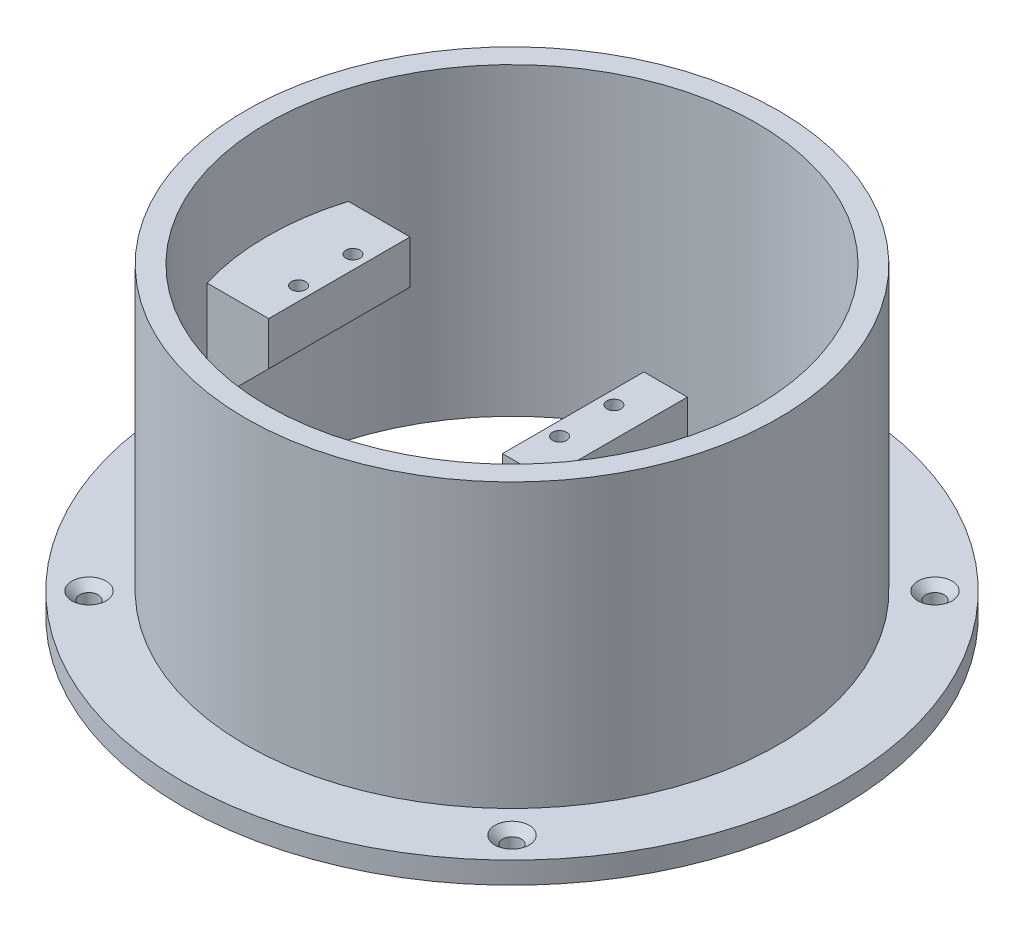
SolidWorks part; units mm, degrees
material "ABS"
ref_plane "Front Plane" through (0, 0, 0) normal (0, 0, 1) x (1, 0, 0)
ref_plane "Top Plane" through (0, 0, 0) normal (0, 1, 0) x (1, 0, 0)
ref_plane "Right Plane" through (0, 0, 0) normal (1, 0, 0) x (0, 0, -1)
sketch "Sketch1" plane through (0, 0, 0) normal (0, 1, 0) x (1, 0, 0)
  circle A0 centre (0, 0) radius 60.625
  circle A1 centre (0, 0) radius 45
  dimension "D1" = 121.25
  dimension "D2" = 90
extrude "Boss-Extrude1" add sketch "Sketch1" along normal blind 4 contours A0
sketch "Sketch2" plane through (0, 4, 0) normal (0, 1, 0) x (1, 0, 0)
  circle A0 centre (0, 0) radius 45 construction
  circle A1 centre (0, 0) radius 45
  circle A2 centre (0, 0) radius 49
  dimension "D1" = 4
extrude "Boss-Extrude2" add sketch "Sketch2" along normal blind 52
ref_plane "Plane1" through (0, 36, 0) normal (0, 1, 0) x (1, 0, 0)
sketch "Sketch4" plane through (0, 0, 0) normal (0, 0, 1) x (1, 0, 0)
  line L0 (-60.625, 0) -> (60.625, 0) construction
  line L1 (11.25, 38) -> (19.25, 38)
  line L2 (11.25, 38) -> (11.25, 0)
  line L3 (11.25, 0) -> (19.25, 0)
  line L4 (19.25, 38) -> (19.25, 0)
  line L5 (49, 56) -> (-49, 56) construction
  line L6 (-45, 56) -> (-45, 4)
  line L7 (-31.75, 38) -> (-46.75, 38)
  line L8 (-31.75, 38) -> (-31.75, 30)
  line L9 (-31.75, 30) -> (-46.75, 30)
  line L10 (-46.75, 38) -> (-46.75, 30)
  line L11 (60.625, 4) -> (-60.625, 4) construction
  line L12 (-31.75, 30) -> (-45, 16.75)
  dimension "D1" = 11.25
  dimension "D2" = 8
  dimension "D3" = 18
  dimension "D4" = 43
  dimension "D5" = 15
  dimension "D6" = 8
  dimension "D7" = 45
  dimension "D8" = 18
extrude "Boss-Extrude4" add sketch "Sketch4" along normal mid plane 26 contours L9 L8 L7 L6 | L12 L9 L6 | L1 L4 L3 L2
sketch "Sketch5" plane through (0, 0, 0) normal (0, -1, 0) x (1, 0, 0)
  line L0 (11.25, 13) -> (29.0674, 34.3524)
  line L1 (11.25, -13) -> (29.0674, -34.3524)
  line L2 (11.25, 13) -> (11.25, -13)
  circle A0 centre (0, 0) radius 45 construction
  arc A1 (29.0674, -34.3524) -> (29.0674, 34.3524) centre (0, 0) ccw
extrude "Boss-Extrude5" add sketch "Sketch5" against normal up to surface (4 mm away) contours L0 A1 L1 L2 up to face at (0, 4, 60.625)
sketch "Sketch7" plane through (0, 38, 0) normal (0, 1, 0) x (1, 0, 0)
  line L0 (-31.75, -13) -> (-31.75, 13) construction
  circle A0 centre (-34.25, 5) radius 1.3
  circle A1 centre (-34.25, -5) radius 1.3
  circle A2 centre (13.75, 5) radius 1.3
  circle A3 centre (13.75, -5) radius 1.3
  dimension "D1" = 2.6
  dimension "D2" = 2.6
  dimension "D3" = 10
  dimension "D4" = 5
  dimension "D5" = 2.5
  dimension "D7" = 48
  dimension "D6" = 2
extrude "Cut-Extrude4" cut sketch "Sketch7" against normal blind 7.2
sketch "Sketch9" plane through (11.25, 0, 0) normal (-1, 0, 0) x (0, 0, 1)
  line L0 (13, 0) -> (-13, 0) construction
  line L1 (-5, 29) -> (5, 29)
  line L2 (-5, 29) -> (-5, 0)
  line L3 (-5, 0) -> (5, 0)
  line L4 (5, 29) -> (5, 0)
  line L5 (-5, 29) -> (5, 0) construction
  line L6 (-5, 0) -> (5, 29) construction
  line L7 (0, 0) -> (0, 29) construction
  line L8 (13, 38) -> (-13, 38) construction
  line L10 (5, 5) -> (-5, 5)
  point P0 (0, 14.5)
  dimension "D1" = 10
  dimension "D2" = 9
  dimension "D3" = 5
extrude "Cut-Extrude7" cut sketch "Sketch9" against normal up to surface (8 mm away) contours L10 L4 L1 L2 up to face at (19.25, 21, 0)
sketch "Sketch12" plane through (0, 4, 0) normal (0, 1, 0) x (1, 0, 0)
  line L5 (27.25, 19.6878) -> (27.25, -19.6878)
  line L6 (27.25, 19.6878) -> (27.25, -19.6878)
  line L9 (24.25, 16.0926) -> (24.25, -16.0926)
  line L10 (19.25, -13) -> (19.25, 13) construction
  line L18 (27.25, -19.6878) -> (29.4795, -22.3597)
  line L19 (29.4795, 22.3597) -> (27.25, 19.6878)
  line L21 (24.25, -16.0926) -> (29.4795, -22.3597)
  line L22 (29.4795, 22.3597) -> (24.25, 16.0926)
  arc A2 (29.4795, -22.3597) -> (29.4795, 22.3597) centre (0, 0) ccw
  arc A3 (29.4795, -22.3597) -> (29.4795, 22.3597) centre (0, 0) ccw
  dimension "D2" = 5
  dimension "D1" = 8
extrude "Cut-Extrude9" cut sketch "Sketch12" against normal through all contours L21 A3 L22 L6 | L6 L22 L9 L21
sketch "Sketch14" plane through (0, 4, 0) normal (0, 1, 0) x (1, 0, 0)
  line L0 (0, 0) -> (-38.8909, 38.8909) construction
  line L1 (11.25, 13) -> (19.25, 13) construction
  circle A0 centre (-38.8909, 38.8909) radius 1.5
  circle A1 centre (38.8909, 38.8909) radius 1.5
  circle A2 centre (38.8909, -38.8909) radius 1.5
  circle A3 centre (-38.8909, -38.8909) radius 1.5
  point P15 (0, 0)
  dimension "D1" = 3
  dimension "D2" = 55
  dimension "D3" = 135
  dimension "D4" = 4
hole_wizard "CSK for M3 Countersunk Flat Head Screw1" positions "Sketch15" profile "Sketch17" countersink size "M3" standard "DIN" end condition up to next
sketch "Sketch15" plane through (0, 4, 0) normal (0, 1, 0) x (1, 0, 0)
  point P0 (-38.8909, 38.8909)
  point P3 (-38.8909, -38.8909)
  point P6 (38.8909, -38.8909)
  point P9 (38.8909, 38.8909)
sketch "Sketch17" plane through (-38.8909, 4, -38.8909) normal (1, 0, 0) x (0, 0, 1)
  line L0 (0, 0) -> (0, 4)
  line L1 (0, 4) -> (1.7, 4)
  line L2 (1.7, 4) -> (1.7, 1.45)
  line L3 (1.7, 1.45) -> (3.15, 0)
  line L5 (3.15, 0) -> (0, 0)
  line L6 (-1.7, 1.45) -> (-3.15, 0) construction
  line L11 (0, -6.35) -> (0, 107.95) construction
  dimension "Thru Hole Dia." = 3.4
  dimension "Thru Hole Depth" = 4
  dimension "Near C'Sink Dia." = 6.3
  dimension "Near C'Sink Angle" = 90
